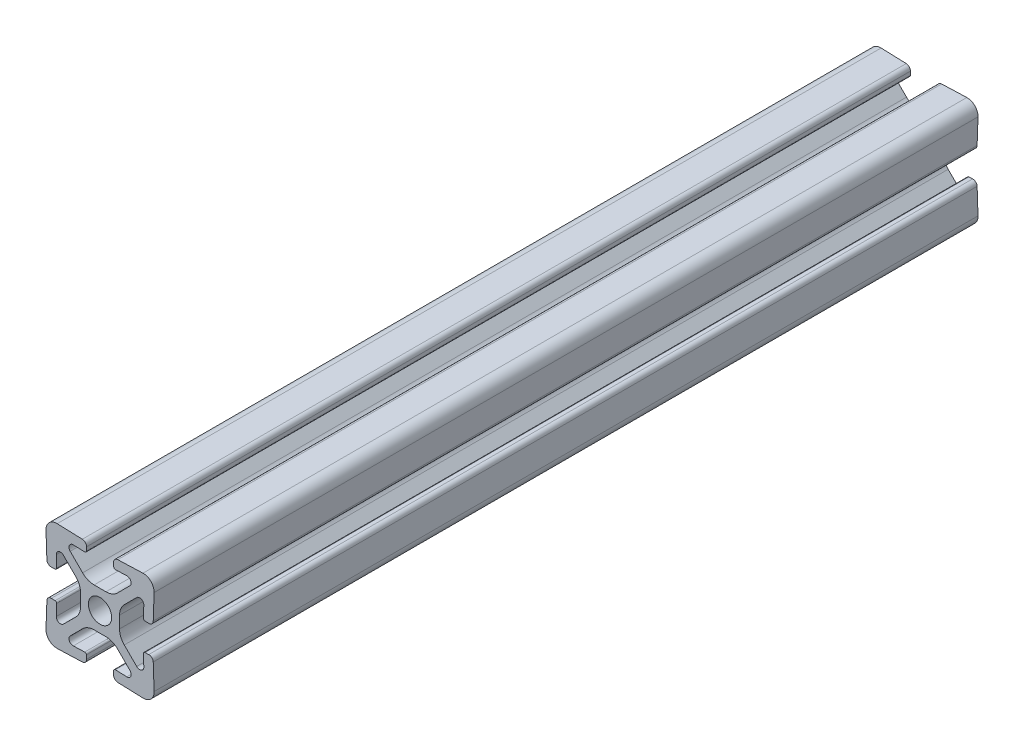
SolidWorks part; units mm, degrees
ref_plane "Front Plane" through (0, 0, 0) normal (0, 0, 1) x (1, 0, 0)
ref_plane "Top Plane" through (0, 0, 0) normal (0, 1, 0) x (1, 0, 0)
ref_plane "Right Plane" through (0, 0, 0) normal (1, 0, 0) x (0, 0, -1)
sketch "Sketch1" plane through (0, 0, 0) normal (0, 0, 1) x (1, 0, 0)
  line L0 (0, 0) -> (0, 10) construction
  line L1 (0, 0) -> (10, 0) construction
  line L2 (0, 0) -> (-10, 10) construction
  line L3 (-7.9302, 9.9988) -> (-3.2721, 9.8361)
  line L4 (-10, 10) -> (0, 10) construction
  line L6 (-2.8352, 8.0198) -> (-4.953, 8.0937)
  line L10 (0, 3.6) -> (-1.1022, 3.6)
  line L11 (-3.2236, 4.4787) -> (-5.5244, 6.7796)
  line L24 (0, 0) -> (-10, 0) construction
  line L25 (-10, 0) -> (0, 0) construction
  line L26 (0, 0) -> (0, -10) construction
  line L27 (-10, -10) -> (-10, 10) construction
  line L28 (0, 10) -> (10, 10) construction
  line L29 (-2.5249, 8.3091) -> (-2.5005, 9.0087)
  line L30 (-10, -10) -> (10, -10) construction
  arc A0 (-9.4142, 9.4142) -> (-7.9302, 9.9988) centre (-8, 8) cw
  arc A5 (-3.2721, 9.8361) -> (-2.5005, 9.0087) centre (-3.3, 9.0366) cw
  arc A6 (-1.1022, 3.6) -> (-3.2236, 4.4787) centre (-1.1022, 6.6) cw
  circle A16 centre (0, 0) radius 2.15
  arc A18 (-5.5244, 6.7796) -> (-4.953, 8.0937) centre (-4.9799, 7.3241) cw
  arc A20 (-2.8352, 8.0198) -> (-2.5249, 8.3091) centre (-2.8247, 8.3196) ccw
  point P15 (0, 0)
  point P42 (-2.3449, 3.6)
  point P80 (-10, 0)
  point P85 (0, -10)
  point P88 (0, -10)
  dimension "D11" = 2
  dimension "D15" = 3
  dimension "Center Hole Diameter" = 4.3
  dimension "D7" = 0.8
  dimension "D8" = 0.3
  dimension "D4" = 0.7701
  dimension "D1" = 45
  dimension "D2" = 2
  dimension "Rail Width" = 20
  dimension "T-Slot Depth" = 6.4
  dimension "D9" = 1.8
  dimension "Rail Height" = 20
  dimension "D23" = 7.2
  dimension "D5" = 11.5
  dimension "T-Slot Width" = 5
  dimension "D3" = 1.775
  dimension "D6" = 9.9598
sketch "Sketch2" plane through (0, 0, 0) normal (1, 0, 0) x (0, 0, -1)
  line L0 (-76.2, 0) -> (76.2, 0)
  line L1 (-76.2, -10) -> (-76.2, 10)
  line L2 (0, 0) -> (0, 10) construction
  line L3 (0, 0) -> (0, 10) construction
  line L4 (76.2, -10) -> (76.2, 10)
  point P0 (-46.2, 0)
  point P3 (0, 0)
  point P7 (46.2, 0)
  point P11 (-76.2, 0)
  point P14 (76.2, 0)
  dimension "D1" = 30
  dimension "Length" = 152.4
sketch "Sketch3" plane through (0, 0, 0) normal (0, 0, 1) x (1, 0, 0)
  line L0 (-2.5249, 8.3091) -> (-2.5005, 9.0087) construction
  line L1 (0, 0) -> (-10, 10) construction
  line L2 (0, 0) -> (-10, 10) construction
  line L5 (-7.9302, 9.9988) -> (-3.2721, 9.8361) construction
  line L6 (-2.8352, 8.0198) -> (-4.953, 8.0937) construction
  line L17 (-2.5249, 8.3091) -> (-2.5005, 9.0087)
  line L19 (-2.8352, 8.0198) -> (-4.953, 8.0937)
  line L20 (0, 0) -> (0, 10) construction
  line L21 (-3.6, 0) -> (-2.15, 0)
  line L22 (-3.6, 0) -> (-3.6, 1.1022)
  line L23 (-4.4787, 3.2236) -> (-6.7796, 5.5244)
  line L42 (-3.2236, 4.4787) -> (-5.5244, 6.7796) construction
  line L43 (0, 3.6) -> (-1.1022, 3.6) construction
  line L44 (-7.9302, 9.9988) -> (-3.2721, 9.8361)
  line L47 (-3.2236, 4.4787) -> (-5.5244, 6.7796)
  line L48 (0, 3.6) -> (-1.1022, 3.6)
  line L59 (0, 3.6) -> (0, 2.15)
  line L60 (-9.9988, 7.9302) -> (-9.8361, 3.2721)
  line L61 (-8.0198, 2.8352) -> (-8.0937, 4.953)
  line L62 (-8.3091, 2.5249) -> (-9.0087, 2.5005)
  arc A0 (-7.9302, 9.9988) -> (-9.4142, 9.4142) centre (-8, 8) ccw construction
  arc A1 (-2.8352, 8.0198) -> (-2.5249, 8.3091) centre (-2.8247, 8.3196) ccw construction
  arc A3 (-2.8352, 8.0198) -> (-2.5249, 8.3091) centre (-2.8247, 8.3196) ccw
  arc A5 (-7.9302, 9.9988) -> (-9.9988, 7.9302) centre (-8, 8) ccw
  circle A13 centre (0, 0) radius 2.15 construction
  arc A14 (0, 2.15) -> (-2.15, 0) centre (0, 0) ccw
  arc A15 (-4.4787, 3.2236) -> (-3.6, 1.1022) centre (-6.6, 1.1022) cw
  arc A16 (-8.0937, 4.953) -> (-6.7796, 5.5244) centre (-7.3241, 4.9799) cw
  arc A17 (-9.0087, 2.5005) -> (-9.8361, 3.2721) centre (-9.0366, 3.3) cw
  arc A18 (-8.0198, 2.8352) -> (-8.3091, 2.5249) centre (-8.3196, 2.8247) cw
  arc A36 (-2.5005, 9.0087) -> (-3.2721, 9.8361) centre (-3.3, 9.0366) ccw construction
  arc A38 (-4.953, 8.0937) -> (-5.5244, 6.7796) centre (-4.9799, 7.3241) ccw construction
  arc A39 (-3.2236, 4.4787) -> (-1.1022, 3.6) centre (-1.1022, 6.6) ccw construction
  arc A41 (-2.5005, 9.0087) -> (-3.2721, 9.8361) centre (-3.3, 9.0366) ccw
  arc A43 (-4.953, 8.0937) -> (-5.5244, 6.7796) centre (-4.9799, 7.3241) ccw
  arc A44 (-3.2236, 4.4787) -> (-1.1022, 3.6) centre (-1.1022, 6.6) ccw
extrude "Boss-Extrude1" add sketch "Sketch3" along normal mid plane 152.4
pattern_circular "CirPattern1" count 4 over 360 about axis through (0, 0, 0) along (0, 0, 1) of "Boss-Extrude1"
ref_plane "Contact Plane 1" through (0, 10, 0) normal (0, 1, 0) x (1, 0, 0)
ref_plane "Contact Plane 2" through (10, 0, 0) normal (1, 0, 0) x (0, 0, -1)
ref_plane "Contact Plane 3" through (0, -10, 0) normal (0, -1, 0) x (-1, 0, 0)
ref_plane "Contact Plane 4" through (-10, 0, 0) normal (-1, 0, 0) x (0, 0, 1)
equation "\"D1@Sketch2\"=\"Rail Width@Sketch1\"*1.5"
equation "\"D1@Boss-Extrude1\" = \"Length@Sketch2\""
